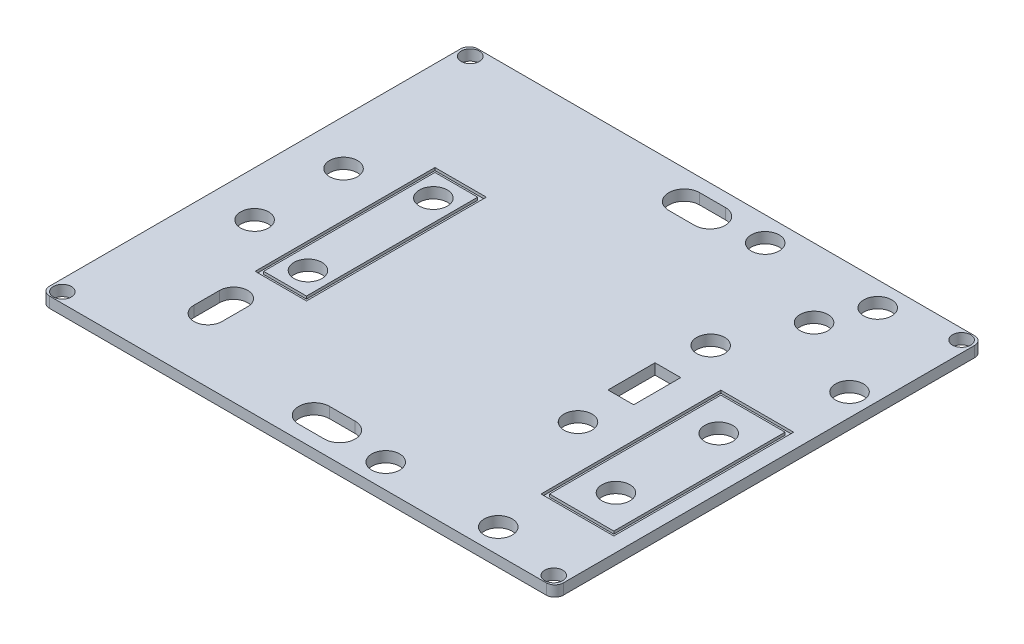
SolidWorks part; units mm, degrees
material "PE High Density Film"
ref_plane "Front Plane" through (0, 0, 0) normal (0, 0, 1) x (1, 0, 0)
ref_plane "Top Plane" through (0, 0, 0) normal (0, 1, 0) x (1, 0, 0)
ref_plane "Right Plane" through (0, 0, 0) normal (1, 0, 0) x (0, 0, -1)
sketch "Sketch1" plane through (0, 0, 0) normal (0, 1, 0) x (1, 0, 0)
  line L1 (-76.2, 63.5) -> (76.2, 63.5)
  line L2 (-76.2, 63.5) -> (-76.2, -63.5)
  line L3 (-76.2, -63.5) -> (76.2, -63.5)
  line L4 (76.2, 63.5) -> (76.2, -63.5)
  line L5 (-76.2, 63.5) -> (76.2, -63.5) construction
  line L6 (-76.2, -63.5) -> (76.2, 63.5) construction
  point P0 (0, 0)
  dimension "D1" = 127
  dimension "D2" = 152.4
extrude "Boss-Extrude1" add sketch "Sketch1" along normal blind 3.175
fillet "Fillet1" radius 2.54 4 edges at (76.2, 1.5875, 63.5) (76.2, 1.5875, -63.5) (-76.2, 1.5875, -63.5) (-76.2, 1.5875, 63.5)
sketch "Sketch9" plane through (0, 0, 0) normal (0, -1, 0) x (1, 0, 0)
  circle A0 centre (60.8584, 30.028) radius 4.15
  circle A1 centre (60.8584, -0.452) radius 4.15
  dimension "D1" = 8.3
  dimension "D2" = 8.3
extrude "Cut-Extrude8" cut sketch "Sketch9" against normal through all
sketch "Sketch12" plane through (0, 0, 0) normal (0, -1, 0) x (1, 0, 0)
  line L0 (-3.81, 54.8882) -> (3.81, 54.8882) construction
  line L1 (-3.81, 59.4656) -> (3.81, 59.4656)
  line L2 (-3.81, 50.3108) -> (3.81, 50.3108)
  line L3 (76.2, 60.96) -> (76.2, -60.96) construction
  arc A0 (-3.81, 59.4656) -> (-3.81, 50.3108) centre (-3.81, 54.8882) ccw
  arc A1 (3.81, 50.3108) -> (3.81, 59.4656) centre (3.81, 54.8882) ccw
  point P2 (0, 54.8882)
  dimension "D1" = 7.62
  dimension "D2" = 76.2
extrude "Cut-Extrude11" cut sketch "Sketch12" against normal through all
mirror "Mirror3" about plane through (0, 0, 0) normal (0, 0, 1) of "Cut-Extrude11"
sketch "Sketch13" plane through (0, 0, 0) normal (0, -1, 0) x (-1, 0, 0)
  line L0 (45.72, -36.83) -> (45.72, -44.45) construction
  line L1 (49.8929, -36.83) -> (49.8929, -44.45)
  line L2 (41.5471, -36.83) -> (41.5471, -44.45)
  line L3 (73.66, -63.5) -> (-73.66, -63.5) construction
  line L4 (76.2, 60.96) -> (76.2, -60.96) construction
  arc A0 (49.8929, -36.83) -> (41.5471, -36.83) centre (45.72, -36.83) ccw
  arc A1 (41.5471, -44.45) -> (49.8929, -44.45) centre (45.72, -44.45) ccw
  point P2 (45.72, -40.64)
  dimension "D1" = 7.62
  dimension "D2" = 19.05
  dimension "D3" = 30.48
extrude "Cut-Extrude12" cut sketch "Sketch13" against normal through all
sketch "Sketch15" plane through (0, 0, 0) normal (0, -1, 0) x (-1, 0, 0)
  circle A0 centre (41.9161, 18.5968) radius 4.15
  circle A1 centre (41.9161, -18.5968) radius 4.15
  dimension "D1" = 8.3
extrude "Cut-Extrude13" cut sketch "Sketch15" against normal through all
sketch "Sketch16" plane through (0, 0, 0) normal (0, -1, 0) x (-1, 0, 0)
  circle A0 centre (-69.5999, 30.4995) radius 4.15
  circle A1 centre (-46.5226, 43.0594) radius 4.15
  dimension "D1" = 8.3
extrude "Cut-Extrude14" cut sketch "Sketch16" against normal through all
sketch "Sketch17" plane through (0, 0, 0) normal (0, -1, 0) x (1, 0, 0)
  circle A0 centre (72.8678, 60.4822) radius 2.69
  dimension "D1" = 5.38
extrude "Cut-Extrude16" cut sketch "Sketch17" against normal through all
mirror "Mirror6" about plane through (0, 0, 0) normal (1, 0, 0) of "Cut-Extrude16"
mirror "Mirror7" about plane through (0, 0, 0) normal (0, 0, 1) of "Mirror6", "Cut-Extrude16"
sketch "Sketch18" plane through (0, 3.175, 0) normal (0, 1, 0) x (1, 0, 0)
  circle A0 centre (37.0789, 21.8539) radius 4.15
  circle A1 centre (37.0789, -17.5085) radius 4.15
  dimension "D1" = 8.3
  dimension "D2" = 8.3
extrude "Cut-Extrude17" cut sketch "Sketch18" against normal through all
sketch "Sketch19" plane through (0, 3.175, 0) normal (0, 1, 0) x (1, 0, 0)
  circle A0 centre (52.1902, -56.2708) radius 4.15
  circle A1 centre (18.821, -56.2708) radius 4.15
  dimension "D1" = 8.3
extrude "Cut-Extrude18" cut sketch "Sketch19" against normal through all
sketch "Sketch20" plane through (0, 3.175, 0) normal (0, 1, 0) x (1, 0, 0)
  circle A0 centre (-62.7988, 12.8363) radius 4.15
  circle A1 centre (-62.7988, -13.5357) radius 4.15
  dimension "D1" = 8.3
extrude "Cut-Extrude19" cut sketch "Sketch20" against normal through all
mirror "Mirror8" about plane through (0, 0, 0) normal (0, 0, 1) of "Cut-Extrude18"
sketch "Sketch21" plane through (0, 0, 0) normal (0, -1, 0) x (1, 0, 0)
  line L0 (33.2689, -27.5727) -> (33.2689, 23.2273) construction
  line L1 (40.8889, 4.8066) -> (33.2689, 4.8066)
  line L2 (40.8889, 4.8066) -> (40.8889, -9.152)
  line L3 (40.8889, -9.152) -> (33.2689, -9.152)
  line L4 (33.2689, 4.8066) -> (33.2689, -9.152)
  line L5 (40.8889, 4.8066) -> (33.2689, -9.152) construction
  line L6 (40.8889, -9.152) -> (33.2689, 4.8066) construction
  point P0 (37.0789, -2.1727)
extrude "Cut-Extrude20" cut sketch "Sketch21" against normal through all
sketch "Sketch22" plane through (0, 3.175, 0) normal (0, 1, 0) x (1, 0, 0)
  line L1 (-35.56, -25.4) -> (-48.26, -25.4)
  line L2 (-35.56, -25.4) -> (-35.56, 25.4)
  line L3 (-35.56, 25.4) -> (-48.26, 25.4)
  line L4 (-48.26, -25.4) -> (-48.26, 25.4)
  line L5 (-34.29, -26.6595) -> (-49.5186, -26.6595)
  line L6 (-34.29, -26.6595) -> (-34.29, 26.67)
  line L7 (-34.29, 26.67) -> (-49.5186, 26.67)
  line L8 (-49.5186, -26.6595) -> (-49.5186, 26.67)
  dimension "D1" = 1.27
  dimension "D2" = 1.2586
  dimension "D3" = 1.27
  dimension "D4" = 1.2595
extrude "Cut-Extrude21" cut sketch "Sketch22" against normal blind 0.7937
sketch "Sketch24" plane through (0, 3.175, 0) normal (0, -1, 0) x (-1, 0, 0)
  line L1 (-70.3834, -40.188) -> (-51.3334, -40.188)
  line L2 (-70.3834, -40.188) -> (-70.3834, 10.612)
  line L3 (-70.3834, 10.612) -> (-51.3334, 10.612)
  line L4 (-51.3334, -40.188) -> (-51.3334, 10.612)
  line L5 (-50.0634, -41.458) -> (-71.6534, -41.458)
  line L6 (-50.0634, -41.458) -> (-50.0634, 11.882)
  line L7 (-50.0634, 11.882) -> (-71.6534, 11.882)
  line L8 (-71.6534, -41.458) -> (-71.6534, 11.882)
  dimension "D1" = 1.27
  dimension "D2" = 1.27
  dimension "D3" = 1.27
  dimension "D4" = 50.8
  dimension "D5" = 1.27
extrude "Cut-Extrude24" cut sketch "Sketch24" along normal blind 0.7937
